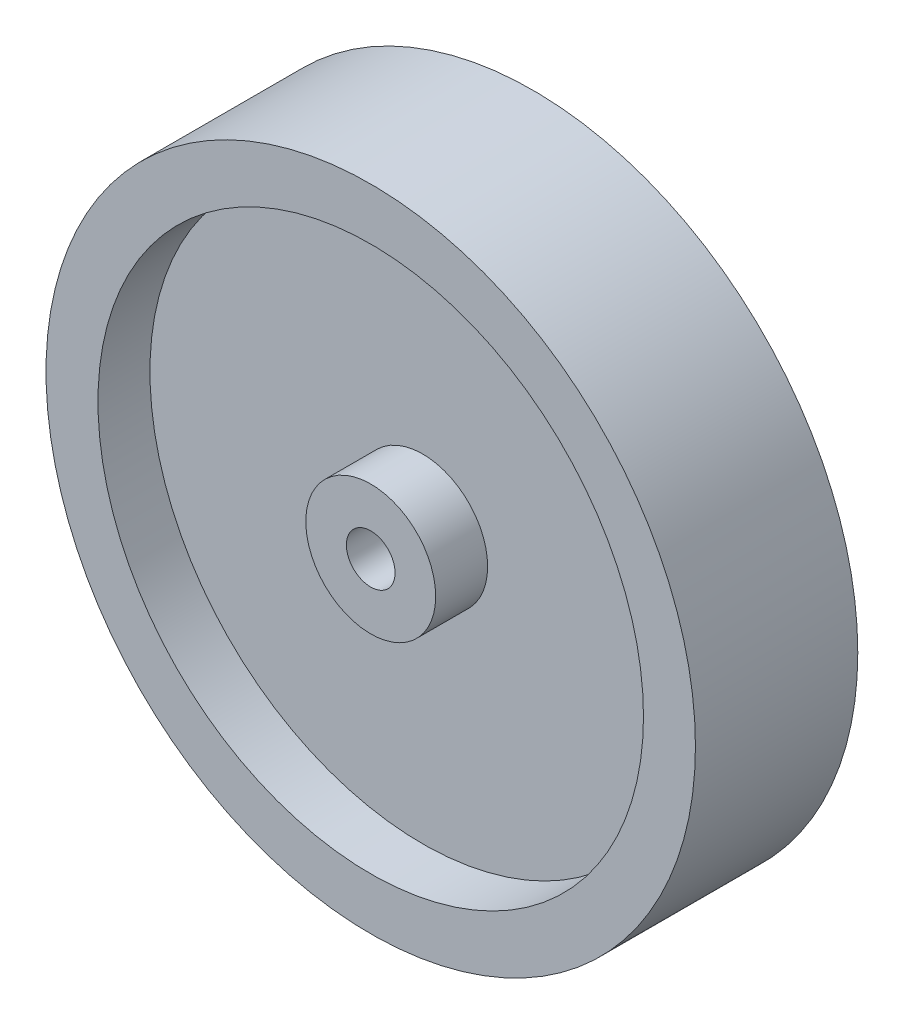
SolidWorks part; units mm, degrees
material "PP Copolymer"
ref_plane "Front Plane" through (0, 0, 0) normal (0, 0, 1) x (1, 0, 0)
ref_plane "Top Plane" through (0, 0, 0) normal (0, 1, 0) x (1, 0, 0)
ref_plane "Right Plane" through (0, 0, 0) normal (1, 0, 0) x (0, 0, -1)
sketch "Sketch1" plane through (0, 0, 0) normal (0, 0, 1) x (1, 0, 0)
  circle A0 centre (0, 0) radius 63.5
  circle A1 centre (0, 0) radius 4.7625
  dimension "D1" = 127
  dimension "D2" = 9.525
extrude "Boss-Extrude1" add sketch "Sketch1" against normal mid plane 31.75
sketch "Sketch2" plane through (0, 0, 15.875) normal (0, 0, 1) x (1, 0, 0)
  circle A0 centre (0, 0) radius 12.7
  circle A1 centre (0, 0) radius 53.34
  dimension "D1" = 106.68
  dimension "D2" = 25.4
extrude "Cut-Extrude1" cut sketch "Sketch2" against normal blind 10.16
mirror "Mirror1" about plane through (0, 0, 0) normal (0, 0, 1) of "Cut-Extrude1"
